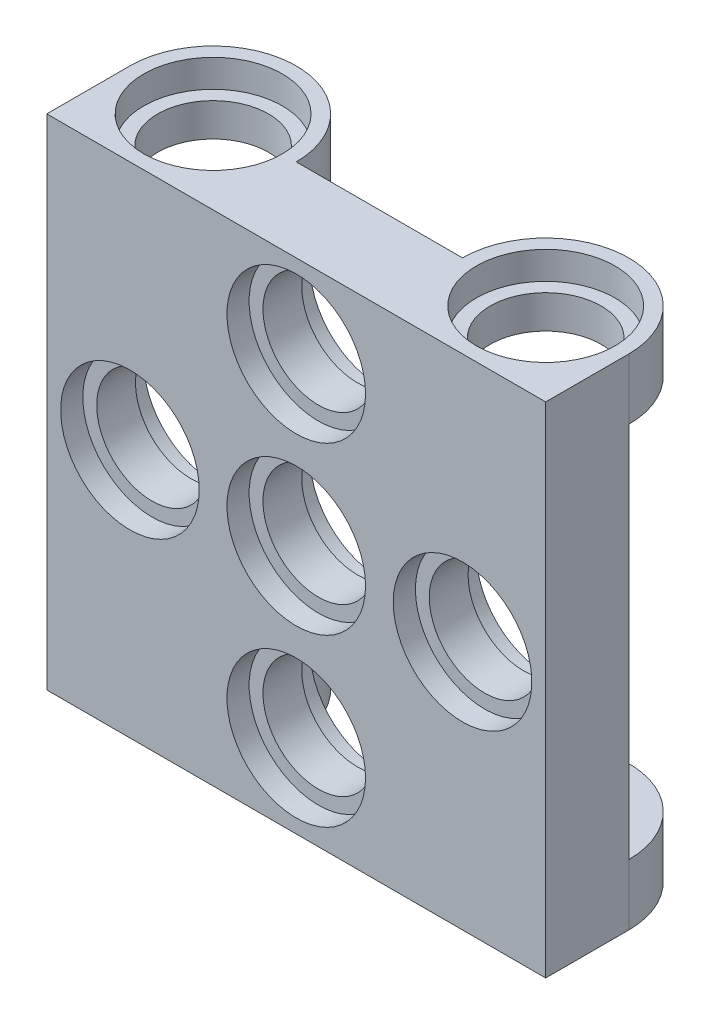
SolidWorks part; units mm, degrees
material "ABS"
ref_plane "Plan de face" through (0, 0, 0) normal (0, 0, 1) x (1, 0, 0)
ref_plane "Plan de dessus" through (0, 0, 0) normal (0, 1, 0) x (1, 0, 0)
ref_plane "Plan de droite" through (0, 0, 0) normal (1, 0, 0) x (0, 0, -1)
sketch "Esquisse1" plane through (0, 0, 0) normal (0, 0, 1) x (1, 0, 0)
  line L1 (0, 0) -> (-9, 0)
  line L2 (0, 0) -> (0, 9)
  line L3 (0, 9) -> (-9, 9)
  line L4 (-9, 0) -> (-9, 9)
  dimension "D1" = 9
  dimension "D2" = 9
extrude "Boss.-Extru.1" add sketch "Esquisse1" along normal blind 3
hole_wizard "Perçage1" positions "Esquisse3" profile "Esquisse2" legacy end condition through all
sketch "Esquisse3" plane through (0, 0, 3) normal (0, 0, 1) x (1, 0, 0)
  line L0 (0, 0) -> (0, 9) construction
  line L1 (-9, 0) -> (0, 0) construction
  point P0 (0, 0)
  point P3 (0, 6)
  point P7 (-6, 0)
  dimension "D1" = 6
  dimension "D2" = 6
sketch "Esquisse2" plane through (0, 0, 3) normal (1, 0, 0) x (0, -1, 0)
  line L0 (0, 0) -> (0, 4.2017)
  line L1 (0, 4.2017) -> (2, 3)
  line L2 (2, 3) -> (2, 0.8)
  line L3 (2, 0.8) -> (2.5, 0.8)
  line L4 (2.5, 0) -> (0, 0)
  line L5 (0, -11.3109) -> (0, 121.1557) construction
  line L6 (0, 4.2017) -> (-2, 3) construction
  line L7 (2.5, 0.8) -> (2.5, 0)
  dimension "Diamètre" = 4
  dimension "Profondeur" = 3
  dimension "Diamètre chambrage" = 5
  dimension "Profondeur chambrage" = 0.8
  dimension "Angle" = 118
sketch "Esquisse4" plane through (0, 9, 0) normal (0, 1, 0) x (1, 0, 0)
  line L0 (0, 0) -> (-9, 0) construction
  line L1 (-9, 0) -> (-3, 0)
  arc A0 (-3, 0) -> (-9, 0) centre (-6, 0) ccw
  dimension "D1" = 6
extrude "Boss.-Extru.2" add sketch "Esquisse4" against normal blind 2.2
hole_wizard "Perçage2" positions "Esquisse6" profile "Esquisse5" legacy
sketch "Esquisse6" plane through (0, 9, 0) normal (0, 1, 0) x (1, 0, 0)
  point P0 (-6, 0)
sketch "Esquisse5" plane through (-6, 9, 0) normal (1, 0, 0) x (0, 0, 1)
  line L0 (0, 0) -> (0, 2.2)
  line L1 (0, 2.2) -> (2, 2.2)
  line L2 (2, 2.2) -> (2, 1)
  line L3 (2, 1) -> (2.5, 1)
  line L4 (2.5, 0) -> (0, 0)
  line L5 (0, -11.3109) -> (0, 121.1557) construction
  line L6 (0, 2.2) -> (-2, 2.2) construction
  line L7 (2.5, 1) -> (2.5, 0)
  dimension "Diamètre" = 4
  dimension "Profondeur" = 2.2
  dimension "Diamètre chambrage" = 5
  dimension "Profondeur chambrage" = 1
  dimension "Angle" = 180
sketch "Esquisse7" plane through (0, 6.8, 0) normal (0, -1, 0) x (1, 0, 0)
  line L0 (-8, 0) -> (-4, 0) construction
  circle A0 centre (-6, 0) radius 2.5
extrude "Enlèv. mat.-Extru.1" cut sketch "Esquisse7" along normal blind 0.8
sketch "Esquisse8" plane through (0, 0, 0) normal (0, 0, -1) x (-1, 0, 0)
  circle A0 centre (0, 0) radius 2.5
  circle A1 centre (6, 0) radius 2.5
  circle A2 centre (0, 6) radius 2.5
  arc A3 (0, 4) -> (0, 8) centre (0, 6) ccw construction
  arc A4 (8, 0) -> (4, 0) centre (6, 0) ccw construction
  dimension "D1" = 5
extrude "Enlèv. mat.-Extru.2" cut sketch "Esquisse8" against normal blind 0.8
mirror "Symétrie4" about plane through (0, 0, 0) normal (1, 0, 0) of bodies 108
mirror "Symétrie5" about plane through (0, 0, 0) normal (0, 1, 0) of bodies 109
equation "\"D2@Esquisse1\"=\"D1@Esquisse1\""
